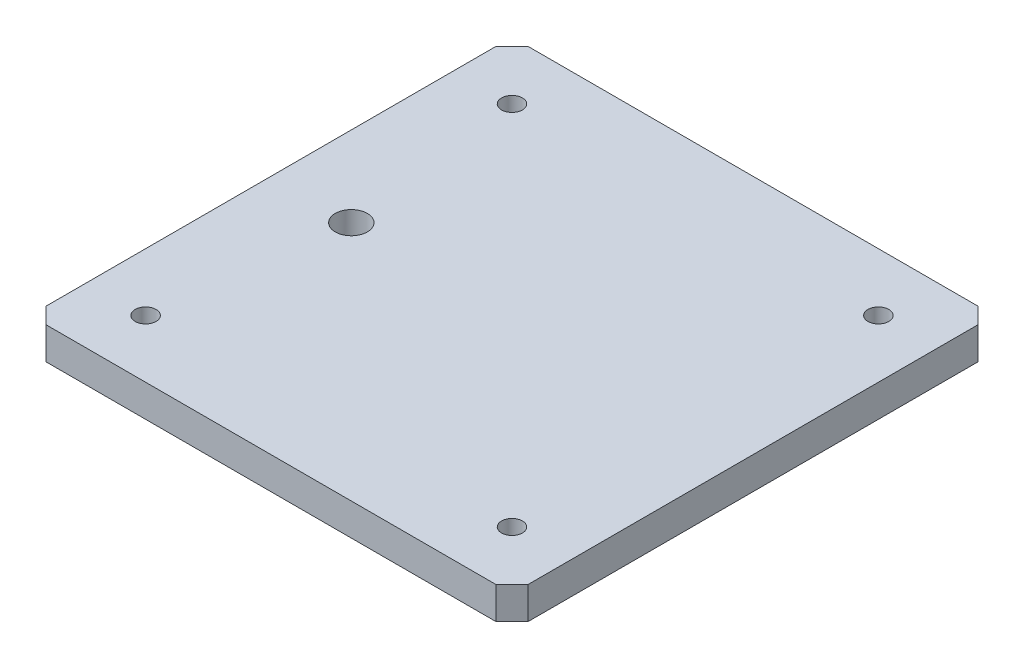
SolidWorks part; units mm, degrees
ref_plane "Front Plane" through (0, 0, 0) normal (0, 0, 1) x (1, 0, 0)
ref_plane "Top Plane" through (0, 0, 0) normal (0, 1, 0) x (1, 0, 0)
ref_plane "Right Plane" through (0, 0, 0) normal (1, 0, 0) x (0, 0, -1)
sketch "Sketch1" plane through (0, 0, 0) normal (0, 1, 0) x (1, 0, 0)
  line L0 (-75, -75) -> (75, 75) construction
  line L1 (-75, -75) -> (75, -75)
  line L2 (-75, -75) -> (-75, 75)
  line L3 (-75, 75) -> (75, 75)
  line L4 (75, -75) -> (75, 75)
  point P4 (0, 0)
  dimension "D1" = 150
  dimension "D2" = 150
extrude "Boss-Extrude1" add sketch "Sketch1" along normal blind 10
chamfer "Chamfer1" distance 5 angle 45 4 edges at (75, 5, -75) (75, 5, 75) (-75, 5, -75) (-75, 5, 75)
hole_wizard "M6 Clearance Hole1" positions "Sketch4" profile "Sketch3" hole size "M6" standard "Ansi Metric" end condition through all
sketch "Sketch4" plane through (0, 10, 0) normal (0, 1, 0) x (-1, 0, 0)
  point P1 (57, -57)
  point P4 (-57, -57)
  point P7 (57, 57)
  point P10 (-57, 57)
sketch "Sketch3" plane through (-57, 10, -57) normal (1, 0, 0) x (0, 0, 1)
  line L0 (0, 0) -> (0, 10)
  line L1 (0, 10) -> (3.25, 10)
  line L2 (3.25, 10) -> (3.25, 0)
  line L5 (3.25, 0) -> (0, 0)
  line L11 (0, -6.35) -> (0, 107.95) construction
  dimension "Thru Hole Dia." = 6.5
  dimension "Thru Hole Depth" = 10
sketch "Sketch2" plane through (0, 10, 0) normal (0, 1, 0) x (1, 0, 0)
  line L0 (-75, 0) -> (-50, 0) construction
  line L1 (-75, 70) -> (-75, -70) construction
  circle A0 centre (-50, 0) radius 5
  dimension "D1" = 10
  dimension "D2" = 20
extrude "Cut-Extrude1" cut sketch "Sketch2" against normal blind 15
